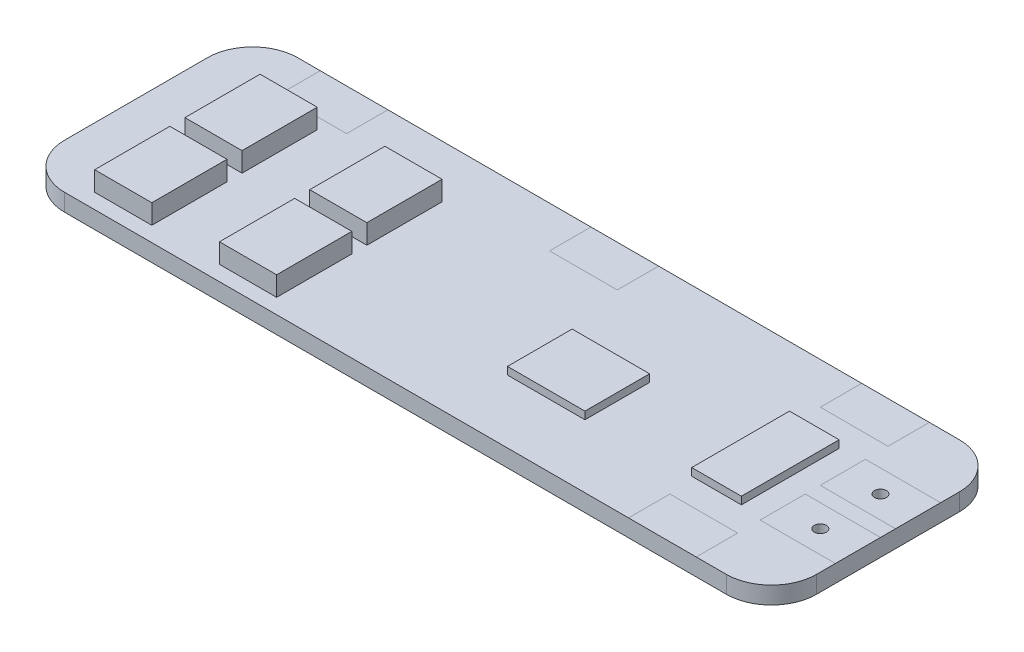
SolidWorks part; units mm, degrees
ref_plane "Alzado" through (0, 0, 0) normal (0, 0, 1) x (1, 0, 0)
ref_plane "Planta" through (0, 0, 0) normal (0, 1, 0) x (1, 0, 0)
ref_plane "Vista lateral" through (0, 0, 0) normal (1, 0, 0) x (0, 0, -1)
sketch "Croquis1" plane through (0, 0, 0) normal (0, 1, 0) x (1, 0, 0)
  line L0 (25, 0) -> (-25, 0) construction
  line L1 (-22, 7.75) -> (22, 7.75)
  line L2 (-25, 4.75) -> (-25, -4.75)
  line L3 (-22, -7.75) -> (22, -7.75)
  line L4 (25, 4.75) -> (25, -4.75)
  line L5 (-25, 7.75) -> (25, -7.75) construction
  line L6 (-25, -7.75) -> (25, 7.75) construction
  circle A0 centre (22.5, 2) radius 0.4
  circle A1 centre (22.5, -2) radius 0.4
  arc A2 (22, -7.75) -> (25, -4.75) centre (22, -4.75) ccw
  arc A3 (-25, -4.75) -> (-22, -7.75) centre (-22, -4.75) ccw
  arc A4 (-22, 7.75) -> (-25, 4.75) centre (-22, 4.75) ccw
  arc A5 (22, 7.75) -> (25, 4.75) centre (22, 4.75) cw
  point P0 (0, 0)
  point P9 (0, 0)
  dimension "D4" = 0.8
  dimension "D6" = 3
  dimension "D1" = 50
  dimension "D2" = 15.5
  dimension "D3" = 2.5
  dimension "D5" = 2
extrude "Saliente-Extruir1" add sketch "Croquis1" along normal blind 1.15
sketch "Croquis2" plane through (0, 1.15, 0) normal (0, 1, 0) x (1, 0, 0)
  line L0 (-25, -1.25) -> (25, -1.25) construction
  line L1 (-25, 4.75) -> (-25, -4.75) construction
  line L2 (25, -4.75) -> (25, 4.75) construction
  line L3 (-14.95, 7.75) -> (-14.95, -7.75) construction
  line L4 (-21, 4.25) -> (-17.2, 4.25)
  line L5 (-21, 4.25) -> (-21, -0.75)
  line L6 (-21, -0.75) -> (-17.2, -0.75)
  line L7 (-17.2, 4.25) -> (-17.2, -0.75)
  line L8 (22, 7.75) -> (-22, 7.75) construction
  line L9 (-22, -7.75) -> (22, -7.75) construction
  line L10 (-8.9, -0.75) -> (-12.7, -0.75)
  line L11 (-12.7, 4.25) -> (-12.7, -0.75)
  line L12 (-8.9, 4.25) -> (-12.7, 4.25)
  line L13 (-8.9, 4.25) -> (-8.9, -0.75)
  line L14 (-8.9, -6.75) -> (-8.9, -1.75)
  line L15 (-8.9, -6.75) -> (-12.7, -6.75)
  line L16 (-12.7, -6.75) -> (-12.7, -1.75)
  line L17 (-8.9, -1.75) -> (-12.7, -1.75)
  line L18 (-21, -1.75) -> (-17.2, -1.75)
  line L19 (-17.2, -6.75) -> (-17.2, -1.75)
  line L20 (-21, -6.75) -> (-17.2, -6.75)
  line L21 (-21, -6.75) -> (-21, -1.75)
  dimension "D1" = 3.8
  dimension "D2" = 5
  dimension "D3" = 4
  dimension "D4" = 2.25
  dimension "D5" = 3.5
  dimension "D6" = 0.5
extrude "Saliente-Extruir2" add sketch "Croquis2" along normal blind 1.3 separate body
sketch "Croquis3" plane through (0, 1.15, 0) normal (0, 1, 0) x (1, 0, 0)
  line L0 (22, 7.75) -> (-22, 7.75) construction
  line L1 (3.25, 0.75) -> (8.4, 0.75)
  line L2 (3.25, 0.75) -> (3.25, -3.55)
  line L3 (3.25, -3.55) -> (8.4, -3.55)
  line L4 (8.4, 0.75) -> (8.4, -3.55)
  line L5 (25, -4.75) -> (25, 4.75) construction
  line L7 (15.2, 3.25) -> (18.5, 3.25)
  line L8 (15.2, 3.25) -> (15.2, -3.25)
  line L9 (15.2, -3.25) -> (18.5, -3.25)
  line L10 (18.5, 3.25) -> (18.5, -3.25)
  point P12 (18.5, 0)
  dimension "D1" = 5.15
  dimension "D2" = 4.3
  dimension "D3" = 7
  dimension "D4" = 16.6
  dimension "D5" = 3.3
  dimension "D6" = 6.5
  dimension "D7" = 6.5
extrude "Saliente-Extruir3" add sketch "Croquis3" along normal blind 0.5 separate body
sketch "Croquis4" plane through (0, 1.15, 0) normal (0, 1, 0) x (1, 0, 0)
  line L0 (25, -4.75) -> (25, 4.75) construction
  line L1 (20, 3.5) -> (25, 3.5)
  line L2 (20, 3.5) -> (20, 0.5)
  line L3 (20, 0.5) -> (25, 0.5)
  line L4 (25, 3.5) -> (25, 0.5)
  line L5 (20, 3.5) -> (25, 0.5) construction
  line L6 (20, 0.5) -> (25, 3.5) construction
  line L7 (25, 0) -> (-25, 0) construction
  line L8 (-25, 4.75) -> (-25, -4.75) construction
  line L9 (22, 7.75) -> (-22, 7.75) construction
  line L10 (15.5, 7.75) -> (20, 7.75)
  line L11 (15.5, 7.75) -> (15.5, 5)
  line L12 (15.5, 5) -> (20, 5)
  line L13 (20, 7.75) -> (20, 5)
  line L14 (-2.5, 7.75) -> (-2.5, 5)
  line L15 (-2.5, 7.75) -> (2, 7.75)
  line L16 (2, 7.75) -> (2, 5)
  line L17 (-2.5, 5) -> (2, 5)
  line L18 (-20.5, 7.75) -> (-20.5, 5)
  line L19 (-20.5, 7.75) -> (-16, 7.75)
  line L20 (-16, 7.75) -> (-16, 5)
  line L21 (-20.5, 5) -> (-16, 5)
  line L22 (15.5, -5) -> (20, -5)
  line L23 (20, -7.75) -> (20, -5)
  line L24 (15.5, -7.75) -> (20, -7.75)
  line L25 (15.5, -7.75) -> (15.5, -5)
  line L26 (20, -0.5) -> (25, -0.5)
  line L27 (25, -3.5) -> (25, -0.5)
  line L28 (20, -3.5) -> (25, -3.5)
  line L29 (20, -3.5) -> (20, -0.5)
  point P0 (22.5, 2)
  point P14 (0, 0)
  point P22 (0, 0)
  dimension "D1" = 3
  dimension "D2" = 4.5
  dimension "D3" = 2.75
  dimension "D5" = 13.5
  dimension "D4" = 3
split line "Línea de partición1"
